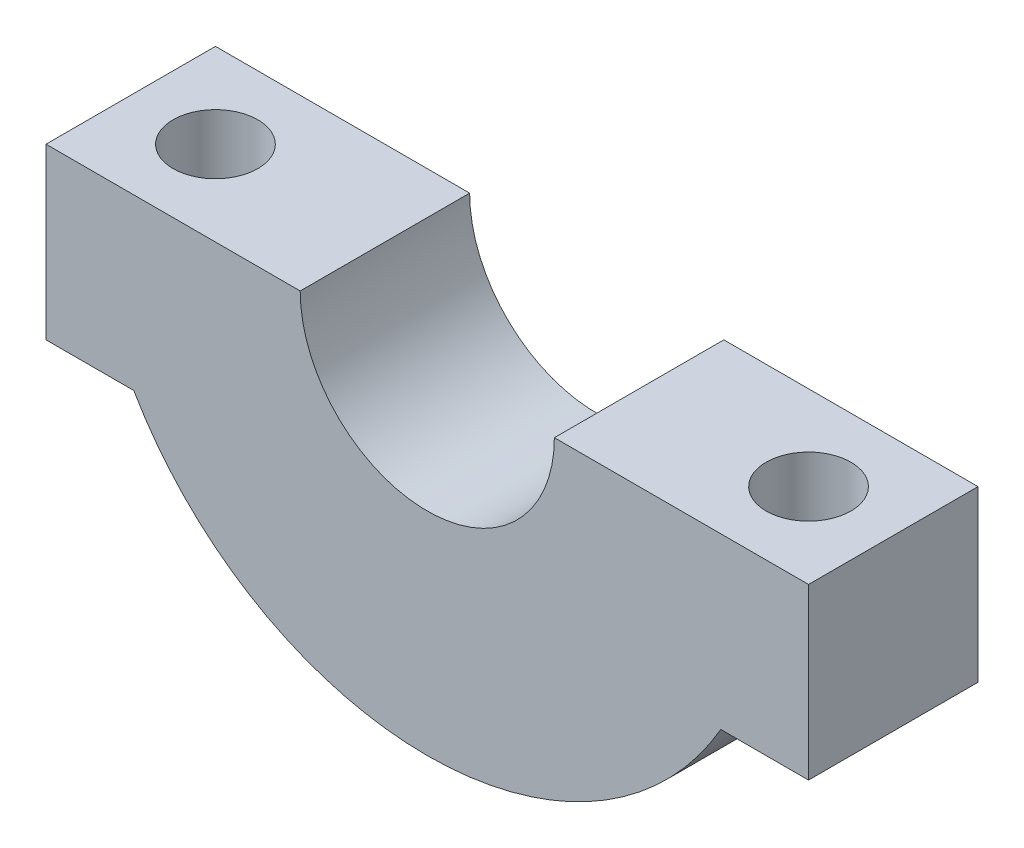
SolidWorks part; units mm, degrees
ref_plane "Front Plane" through (0, 0, 0) normal (0, 0, 1) x (1, 0, 0)
ref_plane "Top Plane" through (0, 0, 0) normal (0, 1, 0) x (1, 0, 0)
ref_plane "Right Plane" through (0, 0, 0) normal (1, 0, 0) x (0, 0, -1)
sketch "Sketch1" plane through (0, 0, 0) normal (0, 0, 1) x (1, 0, 0)
  line L0 (15, 0) -> (45, 0)
  line L1 (45, 0) -> (45, -20)
  line L2 (45, -20) -> (39.4235, -20)
  line L3 (-15, 0) -> (-45, 0)
  line L4 (-45, 0) -> (-45, -20)
  line L5 (-45, -20) -> (-39.4235, -20)
  line L6 (-39.4235, -20) -> (-34.641, -20)
  line L7 (34.641, -20) -> (39.4235, -20)
  arc A0 (-15, 0) -> (15, 0) centre (0, 0) ccw
  arc A2 (-34.641, -20) -> (34.641, -20) centre (0, 0) ccw
  dimension "D2" = 30
  dimension "D3" = 20
  dimension "D4" = 80
  dimension "D1" = 90
extrude "Boss-Extrude1" add sketch "Sketch1" along normal blind 20
hole_wizard "Ø1.0mm Dowel Hole1" positions "Sketch2" profile "Sketch3" hole size "Ø1.0" standard "ISO" end condition through all
sketch "Sketch2" plane through (0, 0, 0) normal (0, 1, 0) x (1, 0, 0)
  line L0 (-35, -10) -> (35, -10) construction
  line L2 (-15, 0) -> (-45, 0) construction
  point P0 (35, -10)
  point P2 (-35, -10)
  dimension "D1" = 10
  dimension "D2" = 70
  dimension "D3" = 35
sketch "Sketch3" plane through (35, 0, 10) normal (1, 0, 0) x (0, 0, 1)
  line L0 (0, 0) -> (0, 40)
  line L1 (0, 40) -> (5, 40)
  line L2 (5, 40) -> (5, 0)
  line L5 (5, 0) -> (0, 0)
  line L11 (0, -6.35) -> (0, 107.95) construction
  dimension "Thru Hole Dia." = 10
  dimension "Thru Hole Depth" = 40
